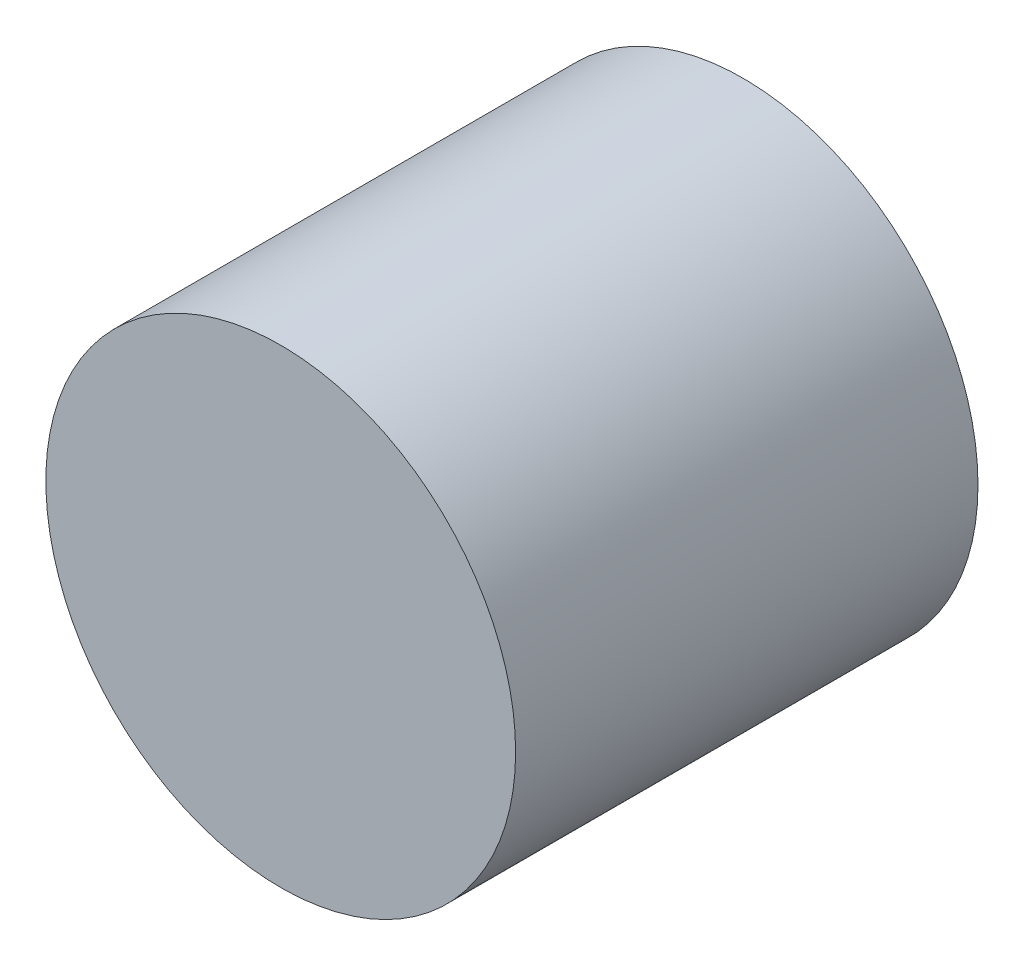
SolidWorks part; units mm, degrees
ref_plane "Alzado" through (0, 0, 0) normal (0, 0, 1) x (1, 0, 0)
ref_plane "Planta" through (0, 0, 0) normal (0, 1, 0) x (1, 0, 0)
ref_plane "Vista lateral" through (0, 0, 0) normal (1, 0, 0) x (0, 0, -1)
sketch "Croquis1" plane through (0, 0, 0) normal (0, 0, 1) x (1, 0, 0)
  circle A0 centre (0, 0) radius 25.4
  dimension "D1" = 50.8
extrude "Saliente-Extruir1" add sketch "Croquis1" along normal blind 50
